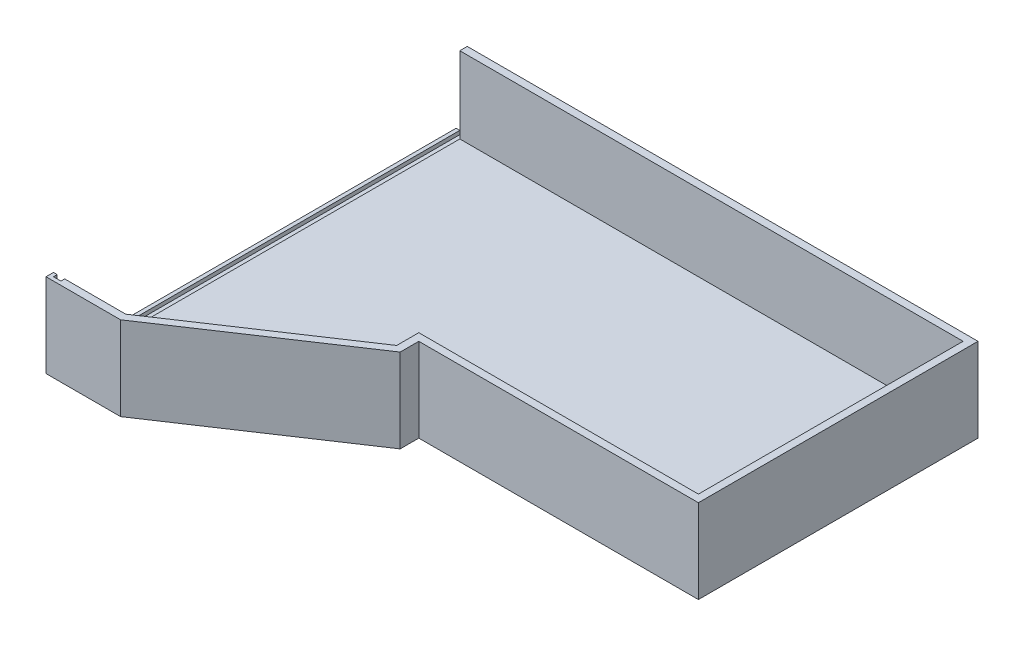
SolidWorks part; units mm, degrees
ref_plane "Front Plane" through (0, 0, 0) normal (0, 0, 1) x (1, 0, 0)
ref_plane "Top Plane" through (0, 0, 0) normal (0, 1, 0) x (1, 0, 0)
ref_plane "Right Plane" through (0, 0, 0) normal (1, 0, 0) x (0, 0, -1)
sketch "ff" plane through (0, 0, 0) normal (0, 1, 0) x (1, 0, 0)
  line L6 (0, -75) -> (0, 0)
  line L7 (-75, -75) -> (0, -75)
  line L8 (-75, -80) -> (-75, -75)
  line L9 (-120, -110) -> (-75, -80)
  line L10 (-140, -110) -> (-120, -110)
  line L11 (-140, 0) -> (-140, -110)
  line L12 (0, 0) -> (-140, 0)
  dimension "D3" = 75
extrude "Boss-Extrude1" add sketch "ff" along normal blind 22.5
sketch "Sketch2" plane through (0, 22.5, 0) normal (0, 1, 0) x (1, 0, 0)
  line L14 (-77, -78.9296) -> (-77, -73)
  line L15 (-77, -73) -> (-2, -73)
  line L16 (-2, -73) -> (-2, -2)
  line L17 (-2, -2) -> (-138, -2)
  line L18 (-138, -2) -> (-138, -108)
  line L19 (-138, -108) -> (-120.6056, -108)
  line L20 (-120.6056, -108) -> (-77, -78.9296)
  line L21 (-77, -78.9296) -> (-77, -73)
  line L22 (-77, -73) -> (-2, -73)
  line L23 (-2, -73) -> (-2, -2)
  line L24 (-2, -2) -> (-138, -2)
  line L25 (-138, -2) -> (-138, -108)
  line L26 (-138, -108) -> (-120.6056, -108)
  line L27 (-120.6056, -108) -> (-77, -78.9296)
  dimension "D1" = 2
extrude "Cut-Extrude5" cut sketch "Sketch2" against normal blind 20.5
sketch "Sketch11" plane through (-138, 0, 0) normal (1, 0, 0) x (0, 0, -1)
  line L1 (-108, 2) -> (-2, 2)
  line L2 (-108, 2) -> (-108, 22.5)
  line L3 (-108, 22.5) -> (-2, 22.5)
  line L4 (-2, 2) -> (-2, 22.5)
extrude "Cut-Extrude6" cut sketch "Sketch11" against normal blind 20.5
sketch "Sketch12" plane through (0, 0, 2) normal (0, 0, 1) x (1, 0, 0)
  line L0 (-2, 2) -> (-140, 2) construction
  line L1 (-140, 22.5) -> (-137, 22.5)
  line L2 (-140, 22.5) -> (-140, 2)
  line L3 (-140, 2) -> (-137, 2)
  line L4 (-137, 22.5) -> (-137, 2)
  dimension "D1" = 3
extrude "Cut-Extrude7" cut sketch "Sketch12" against normal blind 20.5
sketch "Sketch13" plane through (0, 2, 0) normal (0, 1, 0) x (1, 0, 0)
  line L0 (-140, -108) -> (-120.6056, -108) construction
  line L1 (-137, 0) -> (-139, 0)
  line L2 (-137, 0) -> (-137, -108)
  line L3 (-137, -108) -> (-139, -108)
  line L4 (-139, 0) -> (-139, -108)
  dimension "D1" = 2
extrude "Cut-Extrude8" cut sketch "Sketch13" against normal blind 1
sketch "Sketch14" plane through (0, 0, 108) normal (0, 0, -1) x (-1, 0, 0)
  line L0 (140, 22.5) -> (120.6056, 22.5) construction
  line L1 (137, 1) -> (139, 1)
  line L2 (137, 1) -> (137, 22.5)
  line L3 (137, 22.5) -> (139, 22.5)
  line L4 (139, 1) -> (139, 22.5)
extrude "Cut-Extrude9" cut sketch "Sketch14" against normal blind 1
